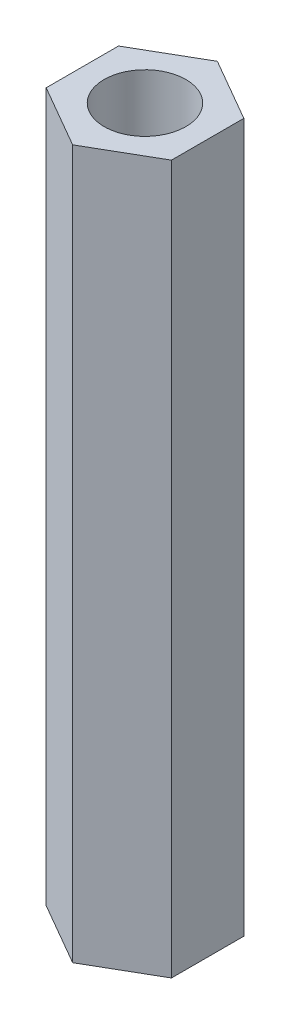
SolidWorks part; units mm, degrees
material "黄铜"
ref_plane "前视基准面" through (0, 0, 0) normal (0, 0, 1) x (1, 0, 0)
ref_plane "上视基准面" through (0, 0, 0) normal (0, 1, 0) x (1, 0, 0)
ref_plane "右视基准面" through (0, 0, 0) normal (1, 0, 0) x (0, 0, -1)
sketch "草图1" plane through (0, 0, 0) normal (0, 1, 0) x (1, 0, 0)
  line L1 (0, 2.6558) -> (-2.3, 1.3279)
  line L2 (-2.3, 1.3279) -> (-2.3, -1.3279)
  line L3 (-2.3, -1.3279) -> (0, -2.6558)
  line L4 (0, -2.6558) -> (2.3, -1.3279)
  line L5 (2.3, -1.3279) -> (2.3, 1.3279)
  line L6 (2.3, 1.3279) -> (0, 2.6558)
  circle A0 centre (0, 0) radius 2.3 construction
  circle A1 centre (0, 0) radius 1.5
  dimension "D2" = 3
  dimension "D1" = 4.6
extrude "凸台-拉伸1" add sketch "草图1" along normal blind 26
